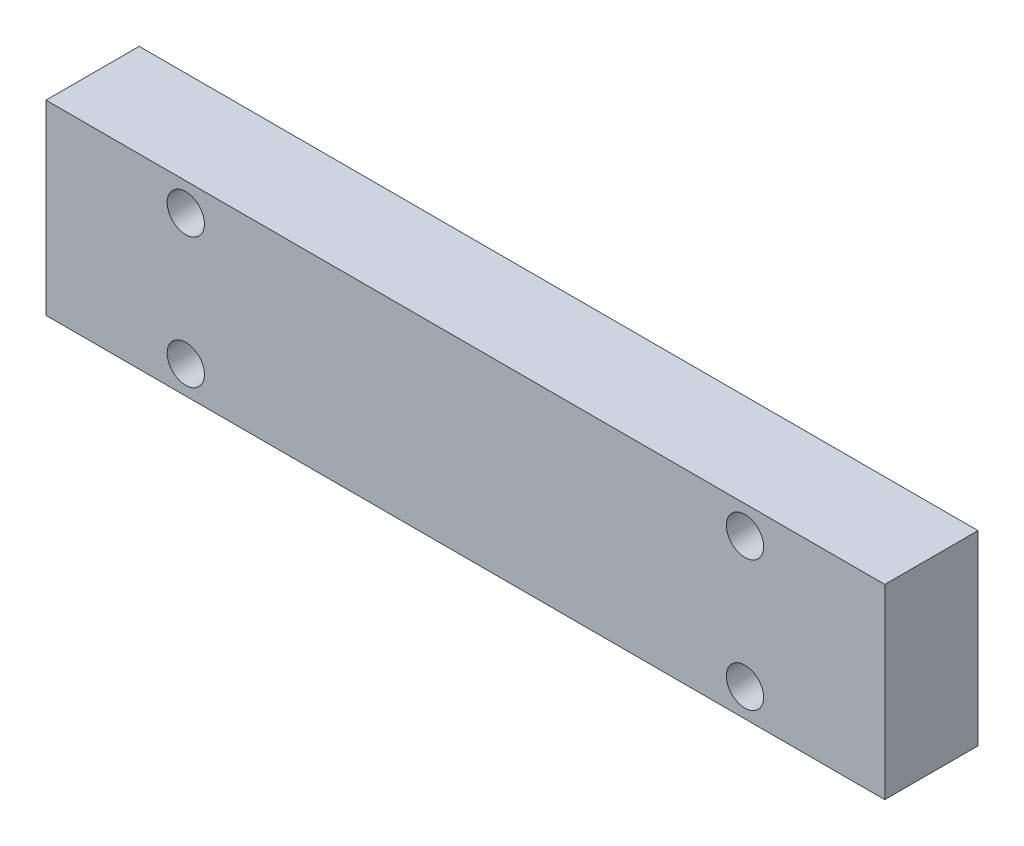
SolidWorks part; units mm, degrees
ref_plane "Plan de face" through (0, 0, 0) normal (0, 0, 1) x (1, 0, 0)
ref_plane "Plan de dessus" through (0, 0, 0) normal (0, 1, 0) x (1, 0, 0)
ref_plane "Plan de droite" through (0, 0, 0) normal (1, 0, 0) x (0, 0, -1)
sketch "Esquisse1" plane through (0, 0, 0) normal (0, 0, 1) x (1, 0, 0)
  line L1 (-61.2842, 27.9464) -> (28.7158, 27.9464)
  line L2 (-61.2842, 27.9464) -> (-61.2842, 7.9464)
  line L3 (-61.2842, 7.9464) -> (28.7158, 7.9464)
  line L4 (28.7158, 27.9464) -> (28.7158, 7.9464)
  dimension "D1" = 90
  dimension "D2" = 20
extrude "Boss.-Extru.1" add sketch "Esquisse1" along normal blind 10
sketch "Esquisse2" plane through (0, 0, 0) normal (0, 0, -1) x (-1, 0, 0)
  line L0 (16.2842, 27.9464) -> (16.2842, 1.2604) construction
  line L3 (-28.7158, 27.9464) -> (61.2842, 27.9464) construction
  line L4 (-13.7158, 34.1671) -> (-13.7158, -6.7897) construction
  line L5 (46.2842, 36.9917) -> (46.2842, -3.2589) construction
  line L6 (61.2842, 7.9464) -> (-28.7158, 7.9464) construction
  circle A0 centre (-13.7158, 24.9464) radius 2
  circle A1 centre (-13.7158, 10.9464) radius 2
  circle A2 centre (46.2842, 10.9464) radius 2
  circle A3 centre (46.2842, 24.9464) radius 2
  dimension "D1" = 30
  dimension "D2" = 30
  dimension "D3" = 4
  dimension "D4" = 4
  dimension "D5" = 3
  dimension "D6" = 3
extrude "Enlèv. mat.-Extru.2" cut sketch "Esquisse2" against normal blind 94
